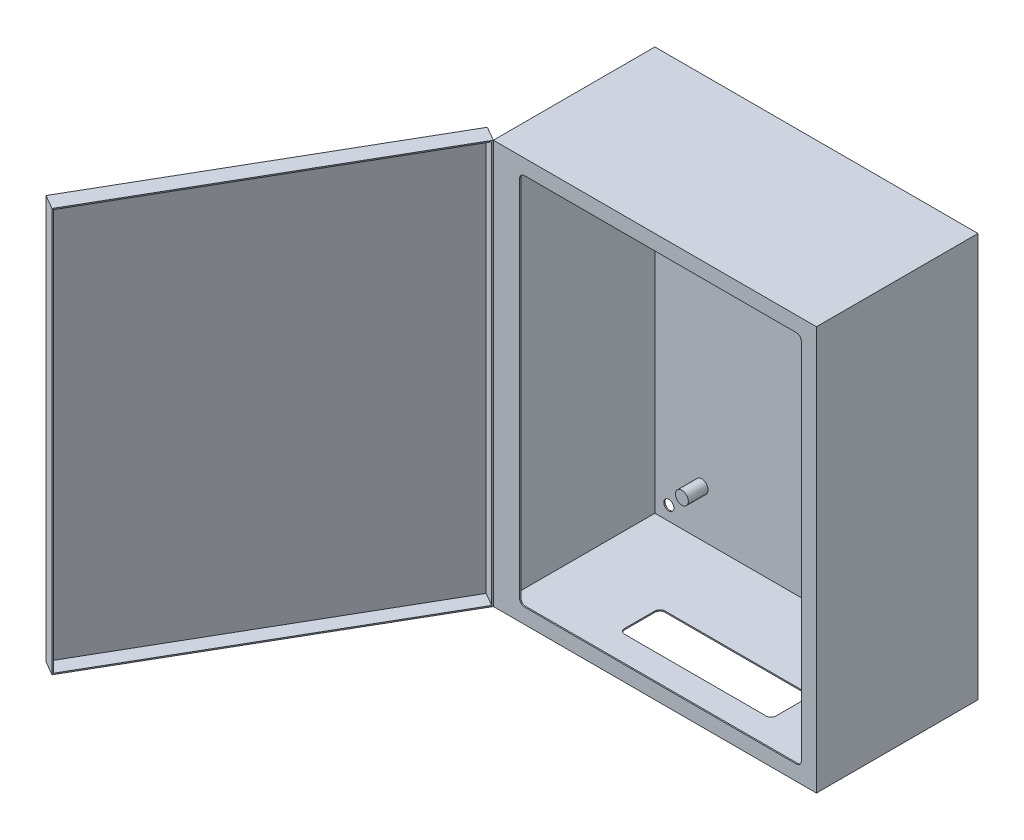
SolidWorks part; units mm, degrees
ref_plane "front" through (0, 0, 0) normal (0, 0, 1) x (1, 0, 0)
ref_plane "top" through (0, 0, 0) normal (0, 1, 0) x (1, 0, 0)
ref_plane "right" through (0, 0, 0) normal (1, 0, 0) x (0, 0, -1)
sketch "Sketch1" plane through (0, 0, 0) normal (0, 0, 1) x (1, 0, 0)
  line L1 (-203.2, 254) -> (203.2, 254)
  line L2 (-203.2, 254) -> (-203.2, -254)
  line L3 (-203.2, -254) -> (203.2, -254)
  line L4 (203.2, 254) -> (203.2, -254)
  point P4 (0, 254)
  point P5 (203.2, 0)
  dimension "D1" = 508
  dimension "D2" = 406.4
extrude "Extrude1" add sketch "Sketch1" along normal blind 203.2
shell "Shell1" thickness 1.524
sketch "Sketch2" plane through (0, 0, 0) normal (0, 0, 1) x (1, 0, 0)
  line L0 (0, 0) -> (53.34, 0) construction
  line L1 (0, 0) -> (0, 49.53) construction
  line L2 (-203.2, -254) -> (203.2, -254) construction
  line L3 (203.2, -254) -> (203.2, 254) construction
  circle A0 centre (184.15, -234.95) radius 6.35
  circle A1 centre (-184.15, -234.95) radius 6.35
  circle A2 centre (184.15, 234.95) radius 6.35
  circle A3 centre (-184.15, 234.95) radius 6.35
  dimension "D3" = 12.7
  dimension "D4" = 368.3
  dimension "D1" = 19.05
  dimension "D2" = 19.05
  dimension "D5" = 469.9
extrude "Cut-Extrude1" cut sketch "Sketch2" along normal through all
sketch "Door angle" plane through (0, 0, 0) normal (0, 1, 0) x (1, 0, 0)
  line L0 (-203.2, -203.2) -> (-287.2626, -348.8007) construction
  line L1 (-287.2626, -348.8007) -> (-265.2655, -361.5007) construction
  line L2 (203.2, -203.2) -> (-203.2, -203.2) construction
  dimension "D1" = 25.4
  dimension "D2" = 120
ref_plane "Door plane" through (-287.2626, 0, 348.8007) normal (0.866, 0, 0.5) x (0.5, 0, -0.866)
sketch "Sketch6" plane through (0, 0, 203.2) normal (0, 0, 1) x (1, 0, 0)
  line L0 (-203.2, 254) -> (-203.2, -254) construction
  line L1 (-163.83, 234.95) -> (177.8, 234.95)
  line L2 (-170.18, 228.6) -> (-170.18, -228.6)
  line L3 (-163.83, -234.95) -> (177.8, -234.95)
  line L4 (184.15, 228.6) -> (184.15, -228.6)
  line L5 (203.2, -254) -> (203.2, 254) construction
  line L6 (203.2, 254) -> (-203.2, 254) construction
  line L7 (-203.2, 254) -> (-203.2, -254)
  line L8 (203.2, 254) -> (-203.2, 254)
  line L9 (-203.2, -254) -> (203.2, -254) construction
  line L10 (-203.2, -254) -> (203.2, -254)
  line L11 (203.2, -254) -> (203.2, 254)
  arc A0 (-163.83, 234.95) -> (-170.18, 228.6) centre (-163.83, 228.6) ccw
  arc A1 (177.8, 234.95) -> (184.15, 228.6) centre (177.8, 228.6) cw
  arc A2 (177.8, -234.95) -> (184.15, -228.6) centre (177.8, -228.6) ccw
  arc A3 (-170.18, -228.6) -> (-163.83, -234.95) centre (-163.83, -228.6) ccw
  point P5 (184.15, 0)
  dimension "D4" = 6.35
  dimension "D1" = 33.02
  dimension "D2" = 19.05
  dimension "D3" = 19.05
extrude "Extrude3" add sketch "Sketch6" against normal blind 1.524
sketch "Sketch4" plane through (-287.2626, 0, 348.8007) normal (0.866, 0, 0.5) x (0.5, 0, -0.866)
  line L0 (168.1252, 0) -> (0, 0) construction
  line L1 (168.1252, 254) -> (-238.2748, 254)
  line L2 (168.1252, 254) -> (168.1252, -254)
  line L3 (168.1252, -254) -> (-238.2748, -254)
  line L4 (-238.2748, 254) -> (-238.2748, -254)
  point P4 (168.1252, 0)
  dimension "D1" = 406.4
  dimension "D2" = 508
extrude "Extrude2" add sketch "Sketch4" against normal blind 20.6375 separate body
shell "Shell2" thickness 1.524
sketch "Sketch7" plane through (-203.2, 0, 0) normal (-1, 0, 0) x (0, 0, 1)
  line L0 (203.2, 254) -> (0, 254) construction
  line L1 (0, 254) -> (0, -254) construction
  line L2 (1.524, 252.476) -> (1.524, -252.476) construction
  circle A0 centre (60.325, 184.15) radius 13.4937
  circle A1 centre (101.6, 50.8) radius 15.4781 construction
  circle A2 centre (86.995, 65.405) radius 2.1082 construction
  circle A3 centre (86.995, 36.195) radius 2.1082 construction
  circle A4 centre (116.205, 36.195) radius 2.1082 construction
  circle A5 centre (116.205, 65.405) radius 2.1082 construction
  point P8 (1.524, 0)
  dimension "D2" = 26.9875
  dimension "D4" = 50.8
  dimension "D6" = 30.9562
  dimension "D7" = 14.605
  dimension "D8" = 14.605
  dimension "D9" = 4.2164
  dimension "D1" = 69.85
  dimension "D3" = 60.325
  dimension "D5" = 101.6
extrude "Cut-Extrude2" cut sketch "Sketch7" against normal blind 2.54
sketch "Sketch8" plane through (0, 0, 0) normal (0, 0, -1) x (-1, 0, 0)
  line L0 (-203.2, 254) -> (203.2, 254) construction
  line L1 (203.2, 254) -> (203.2, -254) construction
  circle A0 centre (127, 177.8) radius 3.175
  dimension "D1" = 6.35
  dimension "D3" = 76.2
  dimension "D2" = 76.2
extrude "Extrude4" [suppressed] add sketch "Sketch8" against normal blind 25.908
sketch "Sketch9" plane through (-82.2844, 0, -47.5069) normal (-0.866, 0, -0.5) x (-0.5, 0, 0.866)
  line L0 (0, 0) -> (123.19, 0) construction
  line L1 (683.9764, 254) -> (683.9764, -254) construction
  circle A0 centre (633.1764, 163.5125) radius 15.875
  circle A1 centre (633.1764, -163.5125) radius 15.875
  dimension "D3" = 31.75
  dimension "D1" = 50.8
  dimension "D2" = 327.025
extrude "Extrude5" add sketch "Sketch9" along normal blind 3.175 draft 10
sketch "Sketch10" plane through (-85.034, 0, -49.0944) normal (-0.866, 0, -0.5) x (-0.5, 0, 0.866)
  line L0 (-9.9437, 0) -> (164.6558, 0) construction
  line L1 (828.7013, -163.8935) -> (828.7013, -163.1315)
  line L2 (437.6515, 163.8935) -> (828.7013, 163.8935)
  line L3 (437.6515, 163.8935) -> (437.6515, 163.1315)
  line L4 (437.6515, 163.1315) -> (828.7013, 163.1315)
  line L5 (828.7013, 163.8935) -> (828.7013, 163.1315)
  line L6 (437.6515, -163.1315) -> (828.7013, -163.1315)
  line L7 (437.6515, -163.8935) -> (437.6515, -163.1315)
  line L8 (437.6515, -163.8935) -> (828.7013, -163.8935)
  point P7 (633.1764, 163.8935)
  point P8 (828.7013, 163.5125)
  point P13 (828.7013, -163.5125)
  point P14 (633.1764, -163.8935)
  dimension "D1" = 0.762
extrude "Cut-Extrude3" cut sketch "Sketch10" against normal blind 1.524
sketch "Sketch11" plane through (0, 0, 0) normal (0, 0, 1) x (1, 0, 0)
  line L0 (0, 0) -> (0, 199.8892) construction
  circle A0 centre (142.875, 193.675) radius 8.128
  circle A1 centre (-142.875, 193.675) radius 8.128
  circle A2 centre (142.875, -193.675) radius 8.128
  circle A3 centre (-142.875, -193.675) radius 8.128
  dimension "D1" = 16.256
  dimension "D3" = 193.675
  dimension "D2" = 142.875
  dimension "D4" = 193.675
extrude "Extrude6" add sketch "Sketch11" along normal blind 26.416
sketch "Sketch12" plane through (0, 0, 0) normal (0, 0, 1) x (1, 0, 0)
  circle A0 centre (101.6, 0) radius 31.75
  circle A1 centre (101.6, -127) radius 31.75
  circle A2 centre (101.6, 127) radius 31.75
  dimension "D1" = 63.5
  dimension "D2" = 127
  dimension "D3" = 101.6
  dimension "D5" = 127
  dimension "D4" = 127
extrude "Cut-Extrude5" cut sketch "Sketch12" along normal blind 2.54
sketch "Sketch13" plane through (0, -254, 0) normal (0, -1, 0) x (1, 0, 0)
  line L0 (-203.2, 0) -> (203.2, 0) construction
  line L1 (-203.2, 203.2) -> (-203.2, 0) construction
  line L2 (-127, 127) -> (-141.605, 141.605) construction
  line L3 (-127, 127) -> (-112.395, 141.605) construction
  line L4 (-50.8, 127) -> (-36.195, 141.605) construction
  line L5 (-50.8, 127) -> (-65.405, 141.605) construction
  line L6 (203.2, 203.2) -> (203.2, 0) construction
  line L7 (25.4, 127) -> (44.3699, 127) construction
  line L9 (16.5047, 128.397) -> (15.3035, 128.397)
  line L11 (16.5047, 125.603) -> (15.3035, 125.603)
  line L12 (15.3035, 128.397) -> (15.3035, 125.603)
  circle A0 centre (127, 127) radius 12.7
  circle A1 centre (-127, 127) radius 15.4813
  circle A2 centre (-141.605, 141.605) radius 1.7843
  circle A3 centre (-112.395, 141.605) radius 1.7844
  circle A4 centre (-112.395, 112.395) radius 1.7844
  circle A5 centre (-141.605, 112.395) radius 1.7843
  circle A6 centre (-65.405, 112.395) radius 1.5875 construction
  circle A7 centre (-65.405, 141.605) radius 1.5875 construction
  circle A8 centre (-36.195, 112.395) radius 1.5875 construction
  circle A9 centre (-50.8, 127) radius 15.4813 construction
  circle A10 centre (-36.195, 141.605) radius 1.5875 construction
  arc A11 (16.5047, 125.603) -> (16.5047, 128.397) centre (25.4, 127) ccw
  point P9 (0, 0)
  point P43 (15.3035, 127)
  dimension "D1" = 25.4
  dimension "D2" = 127
  dimension "D3" = 127
  dimension "D4" = 30.9626
  dimension "D5" = 14.605
  dimension "D6" = 14.605
  dimension "D7" = 3.5687
  dimension "D8" = 127
  dimension "D9" = 76.2
  dimension "D12" = 76.2
  dimension "D13" = 3.175
  dimension "D14" = 14.605
  dimension "D15" = 14.605
  dimension "D16" = 30.9626
  dimension "D17" = 14.605
  dimension "D18" = 14.605
  dimension "D19" = 14.605
  dimension "D20" = 14.605
  dimension "D21" = 14.605
  dimension "D22" = 14.605
  dimension "D23" = 127
  dimension "D24" = 18.0086
  dimension "D26" = 177.8
  dimension "D28" = 19.1008
  dimension "D10" = 90
  dimension "D11" = 20.6546
  dimension "D25" = 127
  dimension "D27" = 2.794
extrude "Bottoml holes" [suppressed] cut sketch "Sketch13" against normal blind 2.54
sketch "Sketch14" plane through (0, -254, 0) normal (0, -1, 0) x (1, 0, 0)
  line L1 (-88.9, 152.4) -> (88.9, 152.4)
  line L2 (-95.25, 146.05) -> (-95.25, 107.95)
  line L3 (-88.9, 101.6) -> (88.9, 101.6)
  line L4 (95.25, 146.05) -> (95.25, 107.95)
  line L5 (-95.25, 127) -> (127.9557, 127) construction
  line L6 (0, 152.4) -> (0, 101.6) construction
  arc A0 (-88.9, 152.4) -> (-95.25, 146.05) centre (-88.9, 146.05) ccw
  arc A1 (88.9, 152.4) -> (95.25, 146.05) centre (88.9, 146.05) cw
  arc A2 (88.9, 101.6) -> (95.25, 107.95) centre (88.9, 107.95) ccw
  arc A3 (-95.25, 107.95) -> (-88.9, 101.6) centre (-88.9, 107.95) ccw
  point P6 (-95.25, 152.4)
  point P9 (95.25, 152.4)
  point P14 (-95.25, 101.6)
  dimension "D3" = 6.35
  dimension "D1" = 190.5
  dimension "D2" = 50.8
  dimension "D4" = 101.6
extrude "Cut-Extrude6" cut sketch "Sketch14" against normal blind 12.7
ref_plane "Plane1" through (0, 0, 127) normal (0, 0, 1) x (1, 0, 0)
